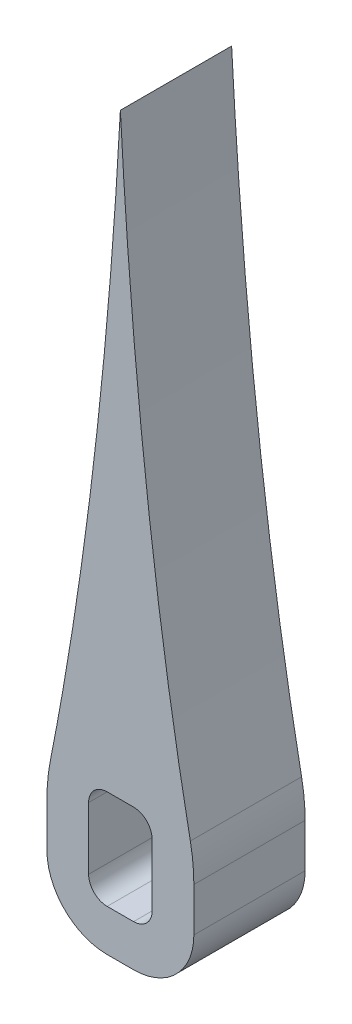
SolidWorks part; units mm, degrees
ref_plane "Front Plane" through (0, 0, 0) normal (0, 0, 1) x (1, 0, 0)
ref_plane "Top Plane" through (0, 0, 0) normal (0, 1, 0) x (1, 0, 0)
ref_plane "Right Plane" through (0, 0, 0) normal (1, 0, 0) x (0, 0, -1)
sketch "Sketch1" plane through (0, 0, 0) normal (0, 0, 1) x (1, 0, 0)
  line L0 (-4.0259, 0.6924) -> (-4.0259, -1.7018)
  line L5 (-1.4859, 2.4638) -> (1.4859, -2.4638) construction
  line L6 (-1.4859, -2.4638) -> (1.4859, 2.4638) construction
  line L7 (-0.7239, -5.0038) -> (0.7239, -5.0038)
  line L8 (4.0259, 0.6924) -> (4.0259, -1.7018)
  line L14 (-1.7399, 1.7018) -> (-1.7399, -1.7018)
  line L15 (-0.7239, -2.7178) -> (0.7239, -2.7178)
  line L16 (1.7399, 1.7018) -> (1.7399, -1.7018)
  line L17 (-0.7239, 2.7178) -> (0.7239, 2.7178)
  arc A4 (-4.0259, -1.7018) -> (-0.7239, -5.0038) centre (-0.7239, -1.7018) ccw
  arc A5 (0.7239, -5.0038) -> (4.0259, -1.7018) centre (0.7239, -1.7018) ccw
  arc A9 (-4.0259, 0.6924) -> (-3.8331, 2.6624) centre (6.1341, 0.6924) cw
  arc A11 (4.0259, 0.6924) -> (3.8331, 2.6624) centre (-6.1341, 0.6924) ccw
  arc A12 (-1.7399, -1.7018) -> (-0.7239, -2.7178) centre (-0.7239, -1.7018) ccw
  arc A13 (0.7239, -2.7178) -> (1.7399, -1.7018) centre (0.7239, -1.7018) ccw
  arc A14 (0.7239, 2.7178) -> (1.7399, 1.7018) centre (0.7239, 1.7018) cw
  arc A15 (-0.7239, 2.7178) -> (-1.7399, 1.7018) centre (-0.7239, 1.7018) ccw
  spline S0 degree 3 poles (-3.8331, 2.6624) (-2.883, 7.4694) (-1.2941, 17.7363) (-0.3276, 29.3087) (0, 35.4212) knots 0.032374 0.032374 0.032374 0.032374 0.516187 1 1 1 1
  spline S1 degree 3 poles (3.8331, 2.6624) (2.883, 7.4694) (1.2941, 17.7363) (0.3276, 29.3087) (0, 35.4212) knots 0.032374 0.032374 0.032374 0.032374 0.516187 1 1 1 1
  point P0 (0, 0)
  dimension "D5" = 10.16
  dimension "D6" = 10.16
  dimension "D1" = 2.9718
  dimension "D2" = 4.9276
extrude "Boss-Extrude2" add sketch "Sketch1" along normal blind 6.096
